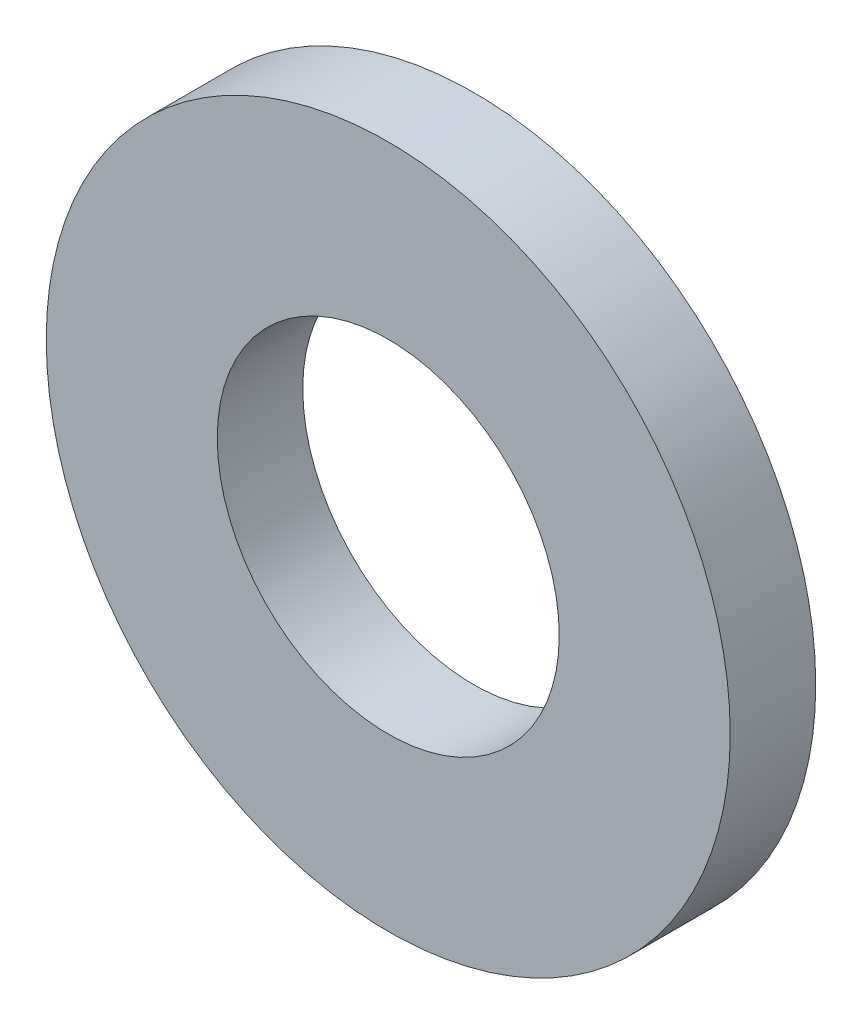
SolidWorks part; units mm, degrees
ref_plane "Přední rovina" through (0, 0, 0) normal (0, 0, 1) x (1, 0, 0)
ref_plane "Horní rovina" through (0, 0, 0) normal (0, 1, 0) x (1, 0, 0)
ref_plane "Pravá rovina" through (0, 0, 0) normal (1, 0, 0) x (0, 0, -1)
sketch "Skica1" plane through (0, 0, 0) normal (0, 0, 1) x (1, 0, 0)
  circle A0 centre (0, 0) radius 3
  circle A1 centre (0, 0) radius 6
  dimension "D1" = 6
  dimension "D2" = 12
extrude "Přidat vysunutím1" add sketch "Skica1" along normal blind 1.5
